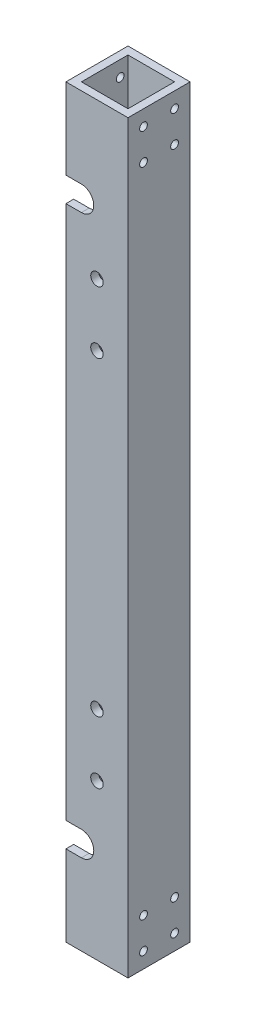
SolidWorks part; units mm, degrees
material "6061 Alloy"
ref_plane "Front" through (0, 0, 0) normal (0, 0, 1) x (1, 0, 0)
ref_plane "Top" through (0, 0, 0) normal (0, 1, 0) x (1, 0, 0)
ref_plane "Right" through (0, 0, 0) normal (1, 0, 0) x (0, 0, -1)
sketch "Sketch1" plane through (0, 0, 0) normal (0, 1, 0) x (1, 0, 0)
  line L1 (-9.525, 9.525) -> (9.525, 9.525)
  line L2 (-9.525, 9.525) -> (-9.525, -9.525)
  line L3 (-9.525, -9.525) -> (9.525, -9.525)
  line L4 (9.525, 9.525) -> (9.525, -9.525)
  line L5 (-9.525, 9.525) -> (9.525, -9.525) construction
  line L6 (-9.525, -9.525) -> (9.525, 9.525) construction
  line L7 (-12.7, 12.7) -> (12.7, 12.7)
  line L8 (-12.7, 12.7) -> (-12.7, -12.7)
  line L9 (-12.7, -12.7) -> (12.7, -12.7)
  line L10 (12.7, 12.7) -> (12.7, -12.7)
  line L11 (-12.7, 12.7) -> (12.7, -12.7) construction
  line L12 (-12.7, -12.7) -> (12.7, 12.7) construction
  point P0 (0, 0)
  point P6 (0, 0)
  dimension "D1" = 25.4
  dimension "D2" = 25.4
  dimension "D3" = 3.175
  dimension "D4" = 3.175
extrude "Boss-Extrude1" add sketch "Sketch1" along normal blind 304.8
sketch "Sketch2" plane through (12.7, 0, 0) normal (1, 0, 0) x (0, 0, -1)
  line L0 (-12.7, 152.4) -> (12.7, 152.4) construction
  line L1 (-9.525, 0) -> (9.525, 0)
  line L2 (-9.525, 0) -> (-9.525, 25.4)
  line L3 (-9.525, 25.4) -> (9.525, 25.4)
  line L4 (9.525, 0) -> (9.525, 25.4)
  line L5 (-12.7, 304.8) -> (-12.7, 0) construction
  line L6 (12.7, 304.8) -> (12.7, 0) construction
  line L7 (9.525, 304.8) -> (9.525, 279.4)
  line L8 (-9.525, 279.4) -> (9.525, 279.4)
  line L9 (-9.525, 304.8) -> (-9.525, 279.4)
  line L10 (-9.525, 304.8) -> (9.525, 304.8)
  dimension "D1" = 25.4
extrude "Cut-Extrude1" [suppressed] cut sketch "Sketch2" against normal through all
sketch "Sketch3" plane through (12.7, 0, 0) normal (1, 0, 0) x (0, 0, -1)
  circle A0 centre (-3.2705, 291.4828) radius 4.9666
extrude "Cut-Extrude2" [suppressed] cut sketch "Sketch3" against normal up to next
sketch "Sketch4" plane through (-12.7, 0, 0) normal (-1, 0, 0) x (0, 0, 1)
  line L0 (-12.7, 266.7) -> (12.7, 266.7) construction
  line L1 (-12.7, 304.8) -> (-12.7, 0) construction
  line L2 (12.7, 304.8) -> (12.7, 0) construction
  line L3 (-12.7, 304.8) -> (12.7, 304.8) construction
  line L4 (-9.525, 280.9875) -> (9.525, 280.9875)
  line L5 (-9.525, 280.9875) -> (-9.525, 252.4125)
  line L6 (-9.525, 252.4125) -> (9.525, 252.4125)
  line L7 (9.525, 280.9875) -> (9.525, 252.4125)
  line L8 (-9.525, 280.9875) -> (9.525, 252.4125) construction
  line L9 (-9.525, 252.4125) -> (9.525, 280.9875) construction
  line L10 (12.7, 152.4) -> (-12.7, 152.4) construction
  line L11 (-9.525, 23.8125) -> (-9.525, 52.3875)
  line L12 (-9.525, 52.3875) -> (9.525, 52.3875)
  line L13 (9.525, 23.8125) -> (9.525, 52.3875)
  line L14 (-9.525, 23.8125) -> (9.525, 23.8125)
  point P6 (0, 266.7)
  dimension "D1" = 19.05
  dimension "D2" = 28.575
  dimension "D3" = 23.8125
extrude "Cut-Extrude3" cut sketch "Sketch4" against normal up to next
hole_wizard "3/8 Clearance Hole1" positions "Sketch5" profile "Sketch6" hole size "3/8" standard "ANSI Inch" end condition through all
sketch "Sketch5" plane through (0, 0, 12.7) normal (0, 0, 1) x (1, 0, 0)
  line L0 (-12.7, 280.9875) -> (-12.7, 252.4125) construction
  line L2 (-12.7, 266.7) -> (-6.35, 266.7) construction
  line L4 (12.7, 152.4) -> (-12.7, 152.4) construction
  line L5 (12.7, 304.8) -> (12.7, 0) construction
  line L6 (-12.7, 304.8) -> (-12.7, 0) construction
  point P0 (-6.35, 266.7)
  point P20 (-6.35, 38.1)
  dimension "D1" = 6.35
sketch "Sketch6" plane through (-6.35, 266.7, 12.7) normal (1, 0, 0) x (0, -1, 0)
  line L0 (0, 0) -> (0, 25.4)
  line L1 (0, 25.4) -> (5.0419, 25.4)
  line L2 (5.0419, 25.4) -> (5.0419, 0)
  line L5 (5.0419, 0) -> (0, 0)
  line L11 (0, -6.35) -> (0, 107.95) construction
  dimension "Thru Hole Dia." = 10.0838
  dimension "Thru Hole Depth" = 25.4
hole_wizard "1/8 (0.125) Diameter Hole1" positions "Sketch7" profile "Sketch8" hole size "1/8" standard "ANSI Inch" end condition through all
sketch "Sketch7" plane through (-12.7, 0, 0) normal (-1, 0, 0) x (0, 0, 1)
  line L0 (0, 304.8) -> (0, 292.1) construction
  line L1 (-12.7, 304.8) -> (12.7, 304.8) construction
  line L2 (0, 292.1) -> (-12.7, 292.1) construction
  line L3 (-12.7, 304.8) -> (-12.7, 0) construction
  line L6 (-6.35, 298.45) -> (6.35, 298.45) construction
  line L7 (-6.35, 298.45) -> (-6.35, 285.75) construction
  line L8 (-6.35, 285.75) -> (6.35, 285.75) construction
  line L9 (6.35, 298.45) -> (6.35, 285.75) construction
  line L10 (-6.35, 298.45) -> (6.35, 285.75) construction
  line L11 (-6.35, 285.75) -> (6.35, 298.45) construction
  line L12 (-12.7, 152.4) -> (12.7, 152.4) construction
  line L13 (12.7, 304.8) -> (12.7, 0) construction
  point P11 (6.35, 285.75)
  point P40 (-6.35, 298.45)
  point P41 (-6.35, 285.75)
  point P42 (6.35, 298.45)
  point P57 (6.35, 19.05)
  point P58 (-6.35, 19.05)
  point P59 (-6.35, 6.35)
  point P60 (6.35, 6.35)
  dimension "D1" = 12.7
sketch "Sketch8" plane through (-12.7, 6.35, 6.35) normal (0, 1, 0) x (0, 0, 1)
  line L0 (0, 0) -> (0, 25.4)
  line L1 (0, 25.4) -> (1.5875, 25.4)
  line L2 (1.5875, 25.4) -> (1.5875, 0)
  line L5 (1.5875, 0) -> (0, 0)
  line L11 (0, -6.35) -> (0, 107.95) construction
  dimension "Thru Hole Dia." = 3.175
  dimension "Thru Hole Depth" = 25.4
hole_wizard "#10 Clearance Hole1" positions "Sketch9" profile "Sketch10" hole size "#10" standard "ANSI Inch" end condition through all
sketch "Sketch9" plane through (0, 0, 12.7) normal (0, 0, 1) x (1, 0, 0)
  point P0 (0, 63.5)
  point P3 (0, 88.9)
  point P6 (0, 241.3)
  point P9 (0, 215.9)
sketch "Sketch10" plane through (0, 63.5, 12.7) normal (1, 0, 0) x (0, -1, 0)
  line L0 (0, 0) -> (0, 25.4)
  line L1 (0, 25.4) -> (2.5527, 25.4)
  line L2 (2.5527, 25.4) -> (2.5527, 0)
  line L5 (2.5527, 0) -> (0, 0)
  line L11 (0, -6.35) -> (0, 107.95) construction
  dimension "Thru Hole Dia." = 5.1054
  dimension "Thru Hole Depth" = 25.4
fillet "Fillet1" radius 4.7625 8 edges at (-11.1125, 23.8125, -9.525) (-11.1125, 52.3875, -9.525) (-11.1125, 52.3875, 9.525) (-11.1125, 23.8125, 9.525) (-11.1125, 252.4125, 9.525) (-11.1125, 252.4125, -9.525) (-11.1125, 280.9875, -9.525) (-11.1125, 280.9875, 9.525)
sketch "Sketch11" plane through (0, 0, 12.7) normal (0, 0, 1) x (1, 0, 0)
  line L0 (-6.35, 266.7) -> (-12.7, 266.7) construction
  line L1 (-12.7, 304.8) -> (-12.7, 0) construction
  line L2 (-6.35, 261.6581) -> (-12.7, 261.6581)
  line L3 (-6.35, 271.7419) -> (-12.7, 271.7419)
  line L4 (-6.35, 38.1) -> (-12.7, 38.1) construction
  line L5 (-6.35, 33.0581) -> (-12.7, 33.0581)
  line L6 (-6.35, 43.1419) -> (-12.7, 43.1419)
  arc A0 (-6.35, 261.6581) -> (-6.35, 271.7419) centre (-6.35, 266.7) ccw
  arc A1 (-12.7, 271.7419) -> (-12.7, 261.6581) centre (-12.7, 266.7) ccw
  arc A2 (-6.35, 33.0581) -> (-6.35, 43.1419) centre (-6.35, 38.1) ccw
  arc A3 (-12.7, 43.1419) -> (-12.7, 33.0581) centre (-12.7, 38.1) ccw
  circle A4 centre (-6.35, 38.1) radius 5.0419 construction
  circle A5 centre (-6.35, 266.7) radius 5.0419 construction
  point P5 (-9.525, 266.7)
  point P10 (-9.525, 38.1)
extrude "Cut-Extrude4" cut sketch "Sketch11" against normal through all
